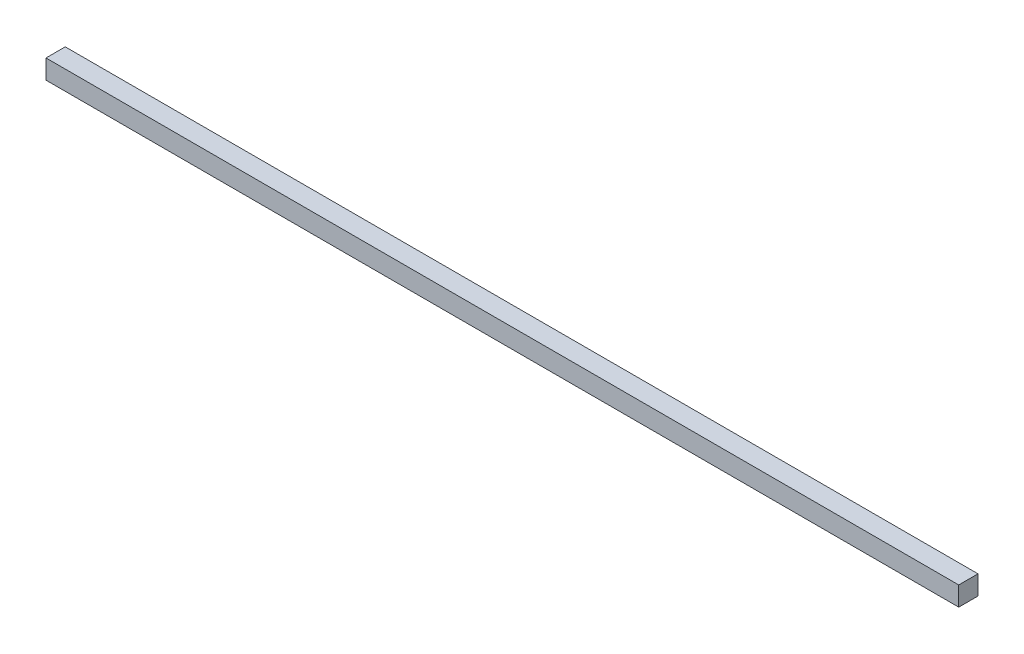
SolidWorks part; units mm, degrees
ref_plane "Front Plane" through (0, 0, 0) normal (0, 0, 1) x (1, 0, 0)
ref_plane "Top Plane" through (0, 0, 0) normal (0, 1, 0) x (1, 0, 0)
ref_plane "Right Plane" through (0, 0, 0) normal (1, 0, 0) x (0, 0, -1)
sketch "Sketch1" plane through (0, 0, 0) normal (1, 0, 0) x (0, 0, -1)
  line L1 (-3.175, 3.175) -> (3.175, 3.175)
  line L2 (-3.175, 3.175) -> (-3.175, -3.175)
  line L3 (-3.175, -3.175) -> (3.175, -3.175)
  line L4 (3.175, 3.175) -> (3.175, -3.175)
  line L5 (-3.175, 3.175) -> (3.175, -3.175) construction
  line L6 (-3.175, -3.175) -> (3.175, 3.175) construction
  point P0 (0, 0)
  dimension "D1" = 6.35
  dimension "D2" = 6.35
extrude "Boss-Extrude1" add sketch "Sketch1" along normal mid plane 300.99
